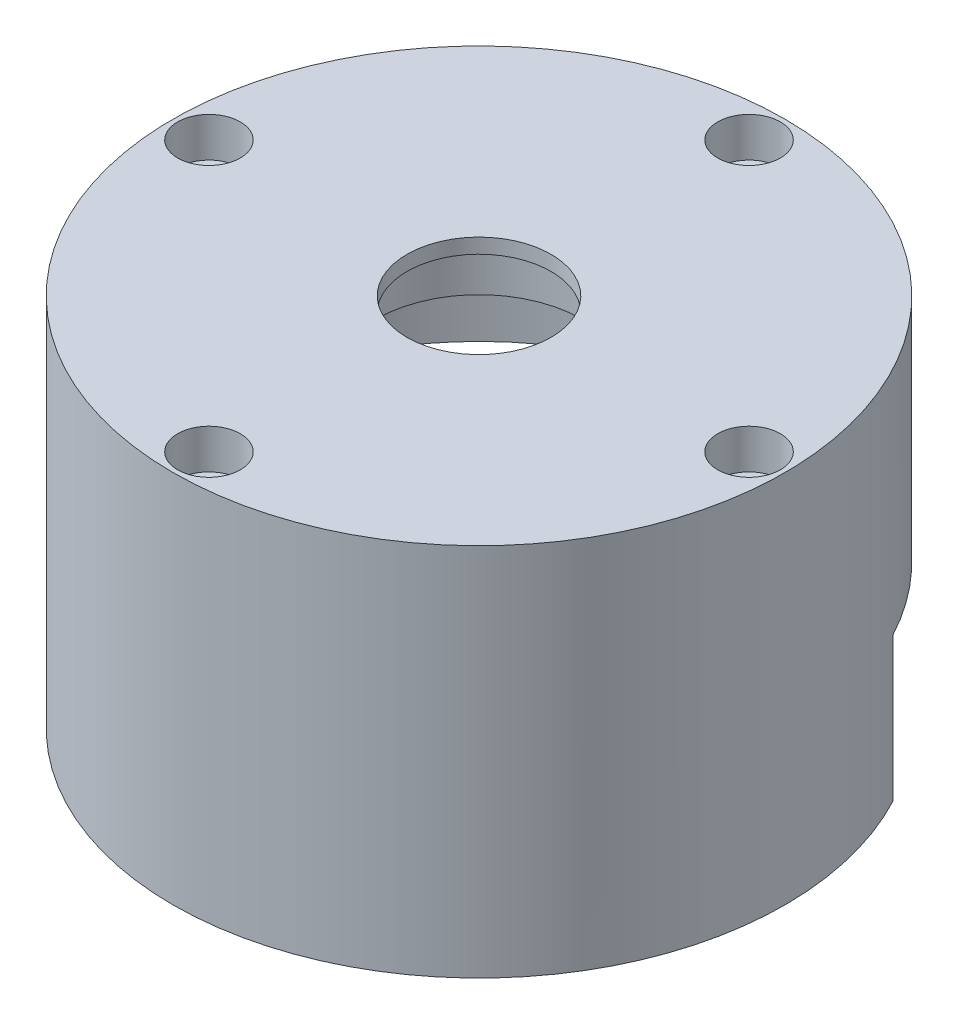
SolidWorks part; units mm, degrees
ref_plane "Front Plane" through (0, 0, 0) normal (0, 0, 1) x (1, 0, 0)
ref_plane "Top Plane" through (0, 0, 0) normal (0, 1, 0) x (1, 0, 0)
ref_plane "Right Plane" through (0, 0, 0) normal (1, 0, 0) x (0, 0, -1)
sketch "Sketch1" plane through (0, 0, 0) normal (0, 1, 0) x (1, 0, 0)
  circle A0 centre (0, 0) radius 42.5
  circle A1 centre (0, 0) radius 10
  circle A2 centre (0, 0) radius 37.5 construction
  circle A3 centre (-37.5, 0) radius 2.55
  circle A4 centre (0, -37.5) radius 2.55
  circle A5 centre (37.5, 0) radius 2.55
  circle A6 centre (0, 37.5) radius 2.55
  dimension "D1" = 85
  dimension "D2" = 20
  dimension "D3" = 75
  dimension "D4" = 5.1
extrude "Boss-Extrude1" add sketch "Sketch1" along normal blind 10 and the other way blind 42
sketch "Sketch2" plane through (0, 0, 0) normal (0, 1, 0) x (1, 0, 0)
  circle A0 centre (0, 0) radius 37.5
  dimension "D1" = 75
extrude "Cut-Extrude1" cut sketch "Sketch2" against normal blind 44
sketch "Sketch3" plane through (0, 0, 0) normal (0, 1, 0) x (1, 0, 0)
  line L3 (-42.5, 0) -> (0, 0) construction
  line L4 (0, 0) -> (42.5, 0) construction
  line L5 (-37.5, 0) -> (-37.5, 48.5355)
  line L6 (-37.5, 48.5355) -> (-12.5, 48.5355)
  line L7 (37.5, 48.5355) -> (37.5, 0)
  line L8 (37.5, 0) -> (-37.5, 0)
  line L9 (-12.5, 48.5355) -> (-12.5, 25.1587)
  line L10 (-12.5, 25.1587) -> (12.5, 25.1587)
  line L11 (12.5, 25.1587) -> (12.5, 48.5355)
  line L12 (0, 37.5) -> (0, 25.1587) construction
  line L13 (12.5, 48.5355) -> (37.5, 48.5355)
  circle A0 centre (0, 0) radius 42.5 construction
  circle A3 centre (0, 0) radius 37.5 construction
  point P22 (0, 0)
  point P23 (0, 0)
  dimension "D1" = 25
extrude "Cut-Extrude2" cut sketch "Sketch3" along normal blind 20 from surface at -42 starting at face at (0, -42, 0)
sketch "Sketch4" plane through (0, 0, 0) normal (0, 1, 0) x (1, 0, 0)
  circle A0 centre (0, 0) radius 14.35
  dimension "D1" = 28.7
extrude "Cut-Extrude3" cut sketch "Sketch4" along normal blind 7.9375 from surface at 0 starting at face at (0, 0, 0)
sketch "Sketch5" plane through (0, 0, 0) normal (0, 1, 0) x (1, 0, 0)
  circle A0 centre (0, 37.5) radius 4.35
  circle A1 centre (37.5, 0) radius 4.35
  circle A2 centre (0, -37.5) radius 4.35
  circle A3 centre (-37.5, 0) radius 4.35
  dimension "D1" = 8.7
extrude "Cut-Extrude4" cut sketch "Sketch5" against normal blind 5.5 from surface at 10 starting at face at (37.5, 10, 2.55)
